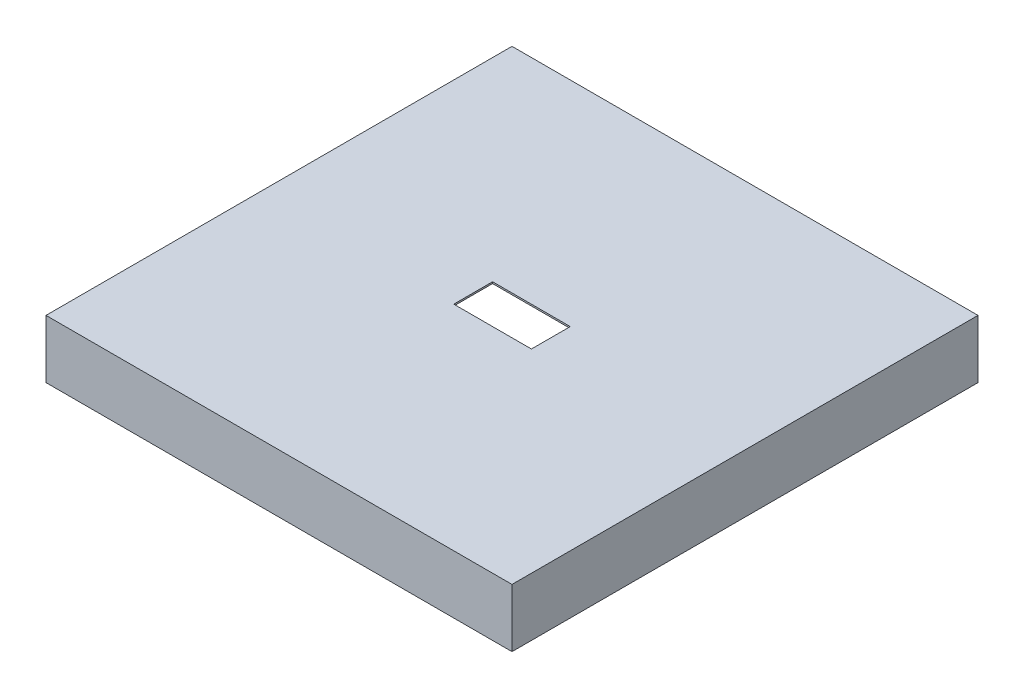
SolidWorks part; units mm, degrees
ref_plane "Front Plane" through (0, 0, 0) normal (0, 0, 1) x (1, 0, 0)
ref_plane "Top Plane" through (0, 0, 0) normal (0, 1, 0) x (1, 0, 0)
ref_plane "Right Plane" through (0, 0, 0) normal (1, 0, 0) x (0, 0, -1)
sketch "Sketch1" plane through (0, 0, 0) normal (0, 1, 0) x (1, 0, 0)
  line L0 (-1739.9, 1739.9) -> (-1739.9, -1739.9)
  line L5 (-1828.8, 1828.8) -> (1828.8, 1828.8)
  line L6 (-1828.8, 1828.8) -> (-1828.8, -1828.8)
  line L7 (-1828.8, -1828.8) -> (1828.8, -1828.8)
  line L8 (1828.8, 1828.8) -> (1828.8, -1828.8)
  line L9 (-1828.8, 1828.8) -> (1828.8, -1828.8) construction
  line L10 (-1828.8, -1828.8) -> (1828.8, 1828.8) construction
  line L11 (-1739.9, -1739.9) -> (1739.9, -1739.9)
  line L12 (1739.9, 1739.9) -> (1739.9, -1739.9)
  line L13 (-1739.9, 1739.9) -> (1739.9, 1739.9)
  point P0 (0, 0)
  dimension "D1" = 3657.6
  dimension "D2" = 88.9
extrude "Boss-Extrude1" add sketch "Sketch1" along normal blind 444.5 contours L8 L5 L6 L7 L0 L13 L12 L11
sketch "Sketch2" plane through (0, 444.5, 0) normal (0, 1, 0) x (1, 0, 0)
  line L4 (1828.8, -1828.8) -> (1828.8, 1828.8)
  line L5 (1828.8, 1828.8) -> (-1828.8, 1828.8)
  line L6 (-1828.8, 1828.8) -> (-1828.8, -1828.8)
  line L7 (-1828.8, -1828.8) -> (1828.8, -1828.8)
  line L8 (1828.8, -1828.8) -> (1828.8, 1828.8)
  line L9 (1828.8, 1828.8) -> (-1828.8, 1828.8)
  line L10 (-1828.8, 1828.8) -> (-1828.8, -1828.8)
  line L11 (-1828.8, -1828.8) -> (1828.8, -1828.8)
  dimension "D1" = 0
extrude "Boss-Extrude2" add sketch "Sketch2" along normal blind 12.7
sketch "Sketch3" plane through (0, 457.2, 0) normal (0, 1, 0) x (1, 0, 0)
  line L1 (-304.8, -152.4) -> (304.8, -152.4)
  line L2 (-304.8, -152.4) -> (-304.8, 152.4)
  line L3 (-304.8, 152.4) -> (304.8, 152.4)
  line L4 (304.8, -152.4) -> (304.8, 152.4)
  line L5 (-304.8, -152.4) -> (304.8, 152.4) construction
  line L6 (-304.8, 152.4) -> (304.8, -152.4) construction
  point P0 (0, 0)
  dimension "D1" = 609.6
  dimension "D2" = 304.8
extrude "Cut-Extrude1" cut sketch "Sketch3" against normal through all
